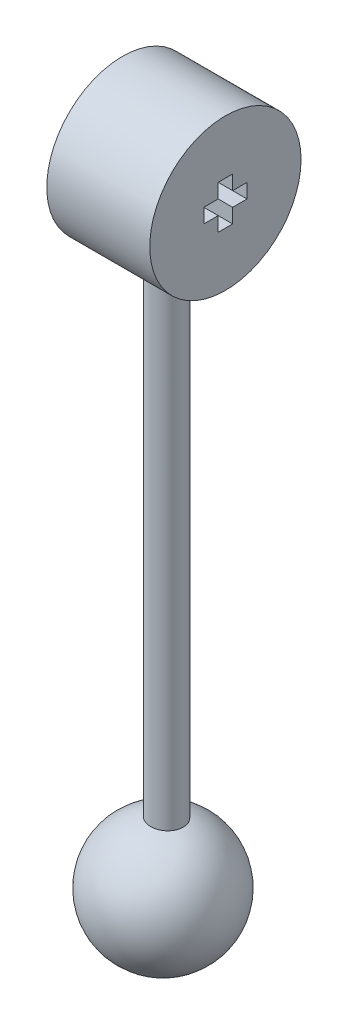
SolidWorks part; units mm, degrees
ref_plane "Front Plane" through (0, 0, 0) normal (0, 0, 1) x (1, 0, 0)
ref_plane "Top Plane" through (0, 0, 0) normal (0, 1, 0) x (1, 0, 0)
ref_plane "Right Plane" through (0, 0, 0) normal (1, 0, 0) x (0, 0, -1)
sketch "Sketch1" plane through (0, 0, 0) normal (0, 1, 0) x (1, 0, 0)
  line L1 (-16.9199, 26.9574) -> (-5.7844, 15.8219) construction
  line L2 (-16.9199, 26.9574) -> (-5.7844, 15.8219)
  arc A1 (-16.9199, 26.9574) -> (-5.7844, 15.8219) centre (-11.3521, 21.3897) cw
  dimension "D2" = 15.748
revolve "Revolve1" add sketch "Sketch1" angle 360 about L1
sketch "Sketch3" plane through (0, 0, 0) normal (0, 1, 0) x (1, 0, 0)
  circle A0 centre (-11.0722, 21.5543) radius 2.0257
extrude "Boss-Extrude1" add sketch "Sketch3" along normal blind 74.168
sketch "Sketch4" plane through (0, 0, 0) normal (1, 0, 0) x (0, 0, -1)
  line L0 (21.5543, 74.168) -> (21.5543, 7.5816) construction
  line L1 (22.4433, 75.946) -> (22.4433, 74.168)
  line L2 (22.4433, 79.502) -> (20.6653, 79.502)
  line L3 (22.4433, 79.502) -> (22.4433, 77.724)
  line L4 (22.4433, 74.168) -> (20.6653, 74.168)
  line L5 (20.6653, 79.502) -> (20.6653, 77.724)
  line L8 (18.8873, 77.724) -> (20.6653, 77.724)
  line L9 (18.8873, 77.724) -> (18.8873, 75.946)
  line L10 (18.8873, 75.946) -> (20.6653, 75.946)
  line L11 (24.2213, 77.724) -> (24.2213, 75.946)
  line L12 (22.4433, 77.724) -> (24.2213, 77.724)
  line L13 (22.4433, 75.946) -> (24.2213, 75.946)
  line L14 (24.2213, 77.724) -> (21.5543, 76.835) construction
  line L15 (21.5543, 76.835) -> (18.8873, 75.946) construction
  line L17 (20.6653, 75.946) -> (20.6653, 74.168)
  line L21 (23.5801, 74.168) -> (19.5286, 74.168) construction
  circle A0 centre (21.5543, 76.835) radius 9.3333
  dimension "D3" = 1.778
extrude "Boss-Extrude5" add sketch "Sketch4" along normal blind 12.7 from offset 16.51 offset against normal yes
